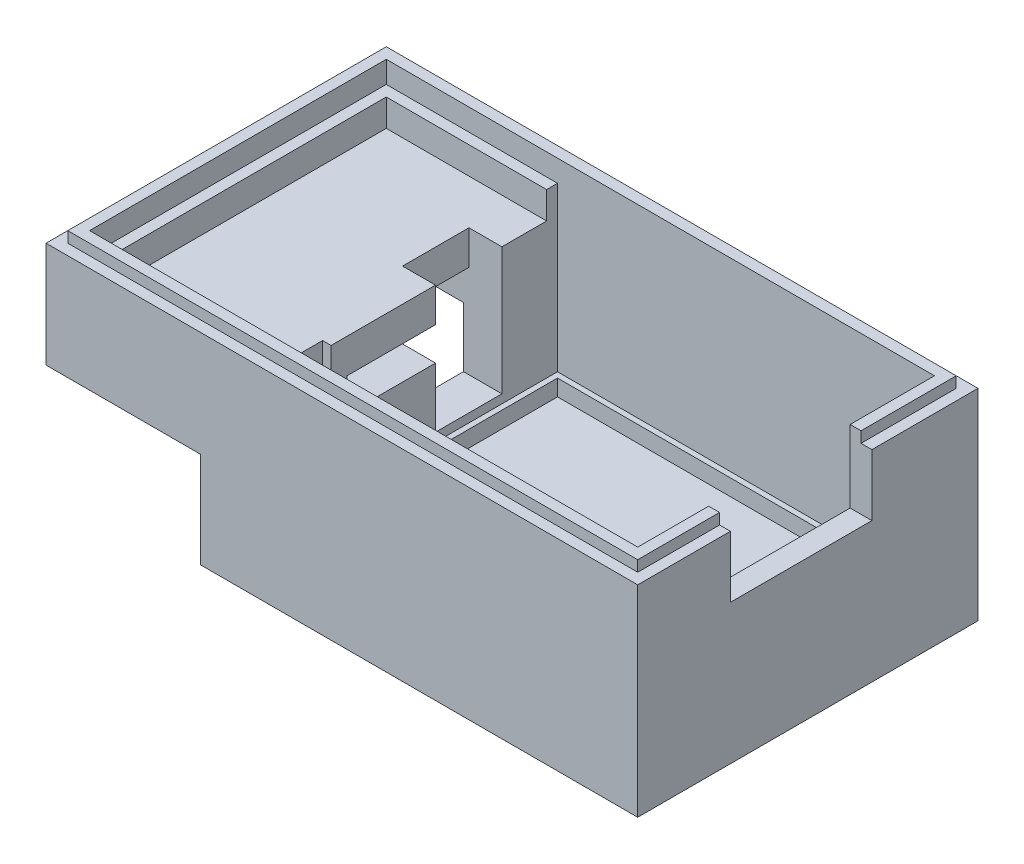
SolidWorks part; units mm, degrees
ref_plane "正面" through (0, 0, 0) normal (0, 0, 1) x (1, 0, 0)
ref_plane "平面" through (0, 0, 0) normal (0, 1, 0) x (1, 0, 0)
ref_plane "右側面" through (0, 0, 0) normal (1, 0, 0) x (0, 0, -1)
sketch "Arduino" plane through (0, 0, 0) normal (0, 1, 0) x (1, 0, 0)
  line L1 (0, 0) -> (68.58, 0)
  line L2 (0, 0) -> (0, 53.34)
  line L3 (0, 53.34) -> (68.58, 53.34)
  line L4 (68.58, 0) -> (68.58, 53.34)
  line L6 (-6.46, 38.12) -> (9.84, 38.12) construction
  line L7 (-0.5, 53.44) -> (68.68, 53.44) construction
  line L8 (-0.5, 53.44) -> (-0.5, -0.1) construction
  line L9 (-0.5, -0.1) -> (68.68, -0.1) construction
  line L10 (68.68, 53.44) -> (68.68, -0.1) construction
  line L11 (-6.46, 44.12) -> (9.84, 44.12)
  line L12 (-6.46, 44.12) -> (-6.46, 32.12)
  line L13 (-6.46, 32.12) -> (9.84, 32.12)
  line L14 (9.84, 44.12) -> (9.84, 32.12)
  line L15 (-1.96, 12.72) -> (11.74, 12.72)
  line L16 (-1.96, 12.72) -> (-1.96, 3.72)
  line L17 (-1.96, 3.72) -> (11.74, 3.72)
  line L18 (11.74, 12.72) -> (11.74, 3.72)
  line L19 (1.69, 44.12) -> (1.69, 32.12) construction
  line L20 (-1.96, 8.22) -> (11.74, 8.22) construction
  line L21 (4.89, 12.72) -> (4.89, 3.72) construction
  line L22 (34.29, 53.34) -> (34.29, 0) construction
  line L23 (-2.06, 12.82) -> (11.84, 12.82) construction
  line L24 (-2.06, 12.82) -> (-2.06, 3.62) construction
  line L25 (-2.06, 3.62) -> (11.84, 3.62) construction
  line L26 (11.84, 12.82) -> (11.84, 3.62) construction
  line L27 (-6.56, 44.22) -> (9.94, 44.22) construction
  line L28 (-6.56, 44.22) -> (-6.56, 32.02) construction
  line L29 (-6.56, 32.02) -> (9.94, 32.02) construction
  line L30 (9.94, 44.22) -> (9.94, 32.02) construction
  line L31 (0, 26.67) -> (68.58, 26.67) construction
  dimension "D1" = 68.58
  dimension "D2" = 53.34
  dimension "D3" = 0.5
  dimension "D4" = 0.1
  dimension "D5" = 0.1
  dimension "D6" = 0.1
  dimension "D7" = 12
  dimension "D8" = 16.3
  dimension "D9" = 11.45
  dimension "D10" = 32.6
  dimension "D11" = 9
  dimension "D12" = 13.7
  dimension "D13" = 29.4
  dimension "D14" = 18.45
  dimension "D15" = 0.1
  dimension "D16" = 0.1
  dimension "D17" = 0.1
  dimension "D18" = 0.1
  dimension "D19" = 0.1
  dimension "D20" = 0.1
  dimension "D21" = 0.1
  dimension "D22" = 0.1
sketch "SDカード" plane through (0, 0, 0) normal (0, 1, 0) x (1, 0, 0)
  line L0 (-0.46, 29.97) -> (25.14, 29.97) construction
  line L1 (-0.46, 43.17) -> (25.14, 43.17)
  line L2 (-0.46, 43.17) -> (-0.46, 16.77)
  line L3 (-0.46, 16.77) -> (25.14, 16.77)
  line L4 (25.14, 43.17) -> (25.14, 16.77)
  line L5 (12.34, 43.17) -> (12.34, 16.77) construction
  line L8 (-0.46, 29.97) -> (-26.3816, 29.97) construction
  line L9 (-0.51, 43.22) -> (25.19, 43.22) construction
  line L10 (-0.51, 43.22) -> (-0.51, 16.72) construction
  line L11 (-0.51, 16.72) -> (25.19, 16.72) construction
  line L12 (25.19, 43.22) -> (25.19, 16.72) construction
  line L14 (0, 26.67) -> (68.58, 26.67) construction
  line L15 (34.29, 53.34) -> (34.29, 0) construction
  dimension "D1" = 26.4
  dimension "D2" = 25.6
  dimension "D3" = 3.3
  dimension "D4" = 21.95
  dimension "D5" = 0.1
  dimension "D6" = 0.1
  dimension "D7" = 0.1
  dimension "D8" = 0.1
sketch "LCD" plane through (0, 0, 0) normal (0, 1, 0) x (1, 0, 0)
  line L0 (-31.77, 22.22) -> (68.84, 22.22) construction
  line L1 (53.23, 37.22) -> (-31.77, 37.22)
  line L2 (53.23, 37.22) -> (53.23, 7.22)
  line L3 (53.23, 7.22) -> (-31.77, 7.22)
  line L4 (-31.77, 37.22) -> (-31.77, 7.22)
  line L5 (68.58, 0) -> (68.58, 53.34) construction
  line L6 (26.34, 37.22) -> (26.34, 7.22) construction
  line L8 (0, 26.67) -> (68.58, 26.67) construction
  dimension "D1" = 4.45
  dimension "D2" = 30
  dimension "D3" = 85
  dimension "D4" = 15.35
sketch "ｽｹｯﾁ6" plane through (0, 0, 0) normal (0, 1, 0) x (1, 0, 0)
  line L0 (-0.5, -0.1) -> (68.68, -0.1) construction
  line L1 (72.78, 58.44) -> (-35.97, 58.44)
  line L2 (72.78, 58.44) -> (72.78, -4.1)
  line L3 (72.78, -4.1) -> (-35.97, -4.1)
  line L4 (-35.97, 58.44) -> (-35.97, -4.1)
  line L6 (-0.5, 53.44) -> (68.68, 53.44) construction
  line L7 (-31.77, 37.22) -> (-31.77, 7.22) construction
  line L9 (68.58, 0) -> (68.58, 53.34) construction
  dimension "D1" = 4
  dimension "D2" = 4.2
  dimension "D3" = 5
  dimension "D4" = 4.2
sketch "ｽｹｯﾁ7" plane through (0, 0, 0) normal (0, 0, 1) x (1, 0, 0)
  line L0 (0, 14.2) -> (-29.2224, 14.2) construction
  line L1 (68.58, 0) -> (0, 0)
  line L2 (68.58, 0) -> (68.58, 1.6)
  line L3 (68.58, 1.6) -> (0, 1.6)
  line L4 (0, 0) -> (0, 1.6)
  line L5 (68.58, 1.6) -> (0, 1.6)
  line L6 (68.58, 1.6) -> (68.58, 12.6)
  line L7 (68.58, 12.6) -> (0, 12.6)
  line L8 (0, 1.6) -> (0, 12.6)
  line L9 (0, 12.6) -> (68.58, 12.6)
  line L10 (0, 12.6) -> (0, 14.2)
  line L11 (0, 14.2) -> (68.58, 14.2)
  line L12 (68.58, 12.6) -> (68.58, 14.2)
  line L13 (68.08, 14.2) -> (63.08, 14.2)
  line L14 (68.08, 14.2) -> (68.08, 25.4)
  line L15 (68.08, 25.4) -> (63.08, 25.4)
  line L16 (63.08, 14.2) -> (63.08, 25.4)
  line L17 (68.88, 25.4) -> (-16.12, 25.4)
  line L18 (68.88, 25.4) -> (68.88, 27)
  line L19 (68.88, 27) -> (-16.12, 27)
  line L20 (-16.12, 25.4) -> (-16.12, 27)
  line L21 (-9.82, 32) -> (61.48, 32)
  line L22 (-9.82, 32) -> (-9.82, 27)
  line L23 (-9.82, 27) -> (61.48, 27)
  line L24 (61.48, 32) -> (61.48, 27)
  line L25 (68.58, 0) -> (0, 0)
  line L26 (68.58, 0) -> (68.58, -3)
  line L27 (68.58, -3) -> (0, -3)
  line L28 (0, 0) -> (0, -3)
  dimension "D1" = 1.6
  dimension "D2" = 11
  dimension "D3" = 1.6
  dimension "D4" = 0.5
  dimension "D5" = 5
  dimension "D6" = 11.2
  dimension "D7" = 1.6
  dimension "D8" = 85
  dimension "D9" = 0.8
  dimension "D10" = 5
  dimension "D11" = 7.4
  dimension "D12" = 71.3
  dimension "D13" = 3
extrude "ﾎﾞｽ - 押し出し1" add sketch "ｽｹｯﾁ6" along normal blind 32 and the other way blind 5
sketch "ｽｹｯﾁ8" plane through (0, 32, 0) normal (0, 1, 0) x (1, 0, 0)
  line L0 (72.78, 58.44) -> (-35.97, 58.44) construction
  line L1 (-31.97, 54.44) -> (68.78, 54.44)
  line L2 (-31.97, 54.44) -> (-31.97, -0.1)
  line L3 (-31.97, -0.1) -> (68.78, -0.1)
  line L4 (68.78, 54.44) -> (68.78, -0.1)
  line L5 (-35.97, 58.44) -> (-35.97, -4.1) construction
  line L6 (-35.97, -4.1) -> (72.78, -4.1) construction
  line L7 (72.78, -4.1) -> (72.78, 58.44) construction
  dimension "D1" = 4
  dimension "D2" = 4
  dimension "D3" = 4
  dimension "D4" = 4
extrude "ｶｯﾄ - 押し出し1" cut sketch "ｽｹｯﾁ8" against normal blind 7
sketch "ｽｹｯﾁ9" plane through (0, 25, 0) normal (0, 1, 0) x (1, 0, 0)
  line L0 (-0.5, 54.44) -> (-0.5, 44.22)
  line L1 (-0.5, 53.44) -> (-0.5, -0.1) construction
  line L2 (-6.56, 44.22) -> (9.94, 44.22) construction
  line L3 (-0.5, 44.22) -> (-6.56, 44.22)
  line L4 (-6.56, 44.22) -> (-6.56, 32.02)
  line L5 (-6.56, 32.02) -> (-0.5, 32.02)
  line L6 (-6.56, 32.02) -> (9.94, 32.02) construction
  line L7 (-0.5, 32.02) -> (-0.5, 12.82)
  line L8 (-2.06, 12.82) -> (11.84, 12.82) construction
  line L9 (-0.5, 12.82) -> (-2.06, 12.82)
  line L10 (-2.06, 12.82) -> (-2.06, 3.62)
  line L11 (-2.06, 3.62) -> (-0.5, 3.62)
  line L12 (-2.06, 3.62) -> (11.84, 3.62) construction
  line L13 (-0.5, 3.62) -> (-0.5, -0.1)
  line L14 (-0.5, -0.1) -> (68.78, -0.1)
  line L15 (68.78, -0.1) -> (68.78, 54.44)
  line L16 (68.78, 54.44) -> (-0.5, 54.44)
extrude "ｶｯﾄ - 押し出し2" cut sketch "ｽｹｯﾁ9" against normal up to vertex (23.4 mm away) up to point (0, 1.6, 0)
sketch "ｽｹｯﾁ10" plane through (0, 1.6, 0) normal (0, 1, 0) x (1, 0, 0)
  line L1 (-0.5, 54.44) -> (68.68, 54.44)
  line L2 (-0.5, 54.44) -> (-0.5, -0.1)
  line L3 (-0.5, -0.1) -> (68.68, -0.1)
  line L4 (68.68, 54.44) -> (68.68, -0.1)
extrude "ｶｯﾄ - 押し出し3" cut sketch "ｽｹｯﾁ10" against normal blind 1.6
sketch "ｽｹｯﾁ11" plane through (0, 0, 0) normal (0, 1, 0) x (1, 0, 0)
  line L1 (0.5, 53.44) -> (67.68, 53.44)
  line L2 (0.5, 53.44) -> (0.5, 0.9)
  line L3 (0.5, 0.9) -> (67.68, 0.9)
  line L4 (67.68, 53.44) -> (67.68, 0.9)
  line L5 (-0.5, 53.44) -> (-0.5, -0.1) construction
  line L6 (-0.5, -0.1) -> (68.68, -0.1) construction
  line L7 (68.68, 53.44) -> (68.68, -0.1) construction
  line L8 (68.78, 54.44) -> (-31.97, 54.44) construction
  dimension "D1" = 1
  dimension "D2" = 1
  dimension "D3" = 1
  dimension "D4" = 1
extrude "ｶｯﾄ - 押し出し4" cut sketch "ｽｹｯﾁ11" against normal blind 3
sketch "ｽｹｯﾁ12" plane through (-6.56, 0, 0) normal (1, 0, 0) x (0, 0, -1)
  line L0 (44.22, 1.6) -> (44.22, 25) construction
  line L1 (32.02, 1.6) -> (44.22, 1.6)
  line L2 (32.02, 1.6) -> (32.02, 12.6)
  line L3 (32.02, 12.6) -> (44.22, 12.6)
  line L4 (44.22, 1.6) -> (44.22, 12.6)
  dimension "D1" = 11
extrude "ｶｯﾄ - 押し出し5" cut sketch "ｽｹｯﾁ12" against normal through all
sketch "ｽｹｯﾁ14" plane through (-35.97, 0, 0) normal (-1, 0, 0) x (0, 0, 1)
  line L0 (-29.97, 18.7) -> (-29.97, 14.2) construction
  line L1 (-44.22, 18.7) -> (-15.72, 18.7)
  line L2 (-44.22, 18.7) -> (-44.22, 14.2)
  line L3 (-44.22, 14.2) -> (-15.72, 14.2)
  line L4 (-15.72, 18.7) -> (-15.72, 14.2)
  line L5 (-44.22, 16.45) -> (-15.72, 16.45) construction
  line L6 (-29.97, 32) -> (-29.97, -5) construction
  line L7 (-58.44, 32) -> (4.1, 32) construction
  line L8 (-58.44, -5) -> (4.1, -5) construction
  line L9 (-58.44, -5) -> (-58.44, 32) construction
  dimension "D1" = 4.5
  dimension "D2" = 28.5
  dimension "D3" = 19.2
extrude "ｶｯﾄ - 押し出し6" cut sketch "ｽｹｯﾁ14" against normal up to next
sketch "ｽｹｯﾁ15" plane through (0, 0, 4.1) normal (0, 0, 1) x (1, 0, 0)
  line L0 (-6.56, 18.7) -> (-6.56, 25) construction
  line L1 (-35.97, -5) -> (-7.56, -5)
  line L2 (-35.97, -5) -> (-35.97, 12.6)
  line L3 (-35.97, 12.6) -> (-7.56, 12.6)
  line L4 (-7.56, -5) -> (-7.56, 12.6)
  line L5 (-35.97, 12.6) -> (-6.56, 12.6) construction
  dimension "D1" = 1
extrude "ｶｯﾄ - 押し出し7" cut sketch "ｽｹｯﾁ15" against normal up to surface (62.54 mm away) up to face at (18.405, 13.5, -58.44)
sketch "ｽｹｯﾁ16" plane through (0, 25, 0) normal (0, 1, 0) x (1, 0, 0)
  line L0 (-0.5, 54.44) -> (-0.5, 44.22) construction
  line L1 (-31.97, 54.44) -> (-0.5, 54.44)
  line L2 (-31.97, 54.44) -> (-31.97, 52.44)
  line L3 (-31.97, 52.44) -> (-0.5, 52.44)
  line L4 (-0.5, 54.44) -> (-0.5, 52.44)
  line L5 (0, 0) -> (0, 53.34) construction
  line L6 (-31.97, -0.1) -> (0, -0.1)
  line L7 (-31.97, -0.1) -> (-31.97, 1.9)
  line L8 (-31.97, 1.9) -> (0, 1.9)
  line L9 (0, -0.1) -> (0, 1.9)
  line L11 (-31.97, 52.44) -> (-29.97, 52.44)
  line L12 (-31.97, 52.44) -> (-29.97, 52.44)
  line L13 (-31.97, 1.9) -> (-29.97, 1.9)
  line L14 (-31.97, 52.44) -> (-31.97, 1.9)
  line L15 (-31.97, 1.9) -> (-29.97, 1.9)
  line L16 (-29.97, 52.44) -> (-29.97, 1.9)
  line M3 (-31.97, 54.44) -> (-31.97, -0.1)
  dimension "D1" = 2
  dimension "D2" = 2
  dimension "D3" = 2
extrude "ﾎﾞｽ - 押し出し2" add sketch "ｽｹｯﾁ16" along normal offset from surface (5 mm away) 2 contours L16 L3 L8 M3 up to face at (18.405, 32, -27.17)
sketch "ｽｹｯﾁ23" plane through (-35.97, 0, 0) normal (-1, 0, 0) x (0, 0, 1)
  line L0 (-58.44, 12.6) -> (4.1, 12.6) construction
  line L1 (-44.22, 14.2) -> (-15.72, 14.2)
  line L2 (-44.22, 14.2) -> (-44.22, 12.6)
  line L3 (-44.22, 12.6) -> (-15.72, 12.6)
  line L4 (-15.72, 14.2) -> (-15.72, 12.6)
  line L5 (-15.72, 14.2) -> (-15.72, 18.7) construction
extrude "ｶｯﾄ - 押し出し14" cut sketch "ｽｹｯﾁ23" against normal up to next
sketch "ｽｹｯﾁ25" plane through (0, 32, 0) normal (0, 1, 0) x (1, 0, 0)
  line L0 (72.78, 58.44) -> (-35.97, 58.44) construction
  line L1 (-33.97, -2.1) -> (70.78, -2.1)
  line L2 (-33.97, -2.1) -> (-33.97, 56.44)
  line L3 (-33.97, 56.44) -> (70.78, 56.44)
  line L4 (70.78, -2.1) -> (70.78, 56.44)
  line L5 (72.78, -4.1) -> (72.78, 58.44) construction
  line L6 (-35.97, -4.1) -> (72.78, -4.1) construction
  line L7 (-35.97, 58.44) -> (-35.97, -4.1) construction
  line L9 (-31.97, -0.1) -> (68.78, -0.1)
  line L10 (-31.97, -0.1) -> (-31.97, 54.44)
  line L11 (-31.97, 54.44) -> (68.78, 54.44)
  line L12 (68.78, -0.1) -> (68.78, 54.44)
  dimension "D1" = 2
  dimension "D2" = 2
  dimension "D3" = 2
  dimension "D4" = 2
extrude "ﾎﾞｽ - 押し出し3" add sketch "ｽｹｯﾁ25" along normal blind 2
sketch "ｽｹｯﾁ26" plane through (68.78, 0, 0) normal (-1, 0, 0) x (0, 0, 1)
  line L0 (0.1, 34) -> (-54.44, 34) construction
  line L1 (-38.94, 34) -> (-12.94, 34)
  line L2 (-38.94, 34) -> (-38.94, 20.7)
  line L3 (-38.94, 20.7) -> (-12.94, 20.7)
  line L4 (-12.94, 34) -> (-12.94, 20.7)
  line L5 (-58.44, -5) -> (-58.44, 32) construction
  line L6 (4.1, -5) -> (-58.44, -5) construction
  dimension "D1" = 19.5
  dimension "D2" = 26
  dimension "D3" = 25.7
extrude "ｶｯﾄ - 押し出し15" cut sketch "ｽｹｯﾁ26" against normal blind 4
